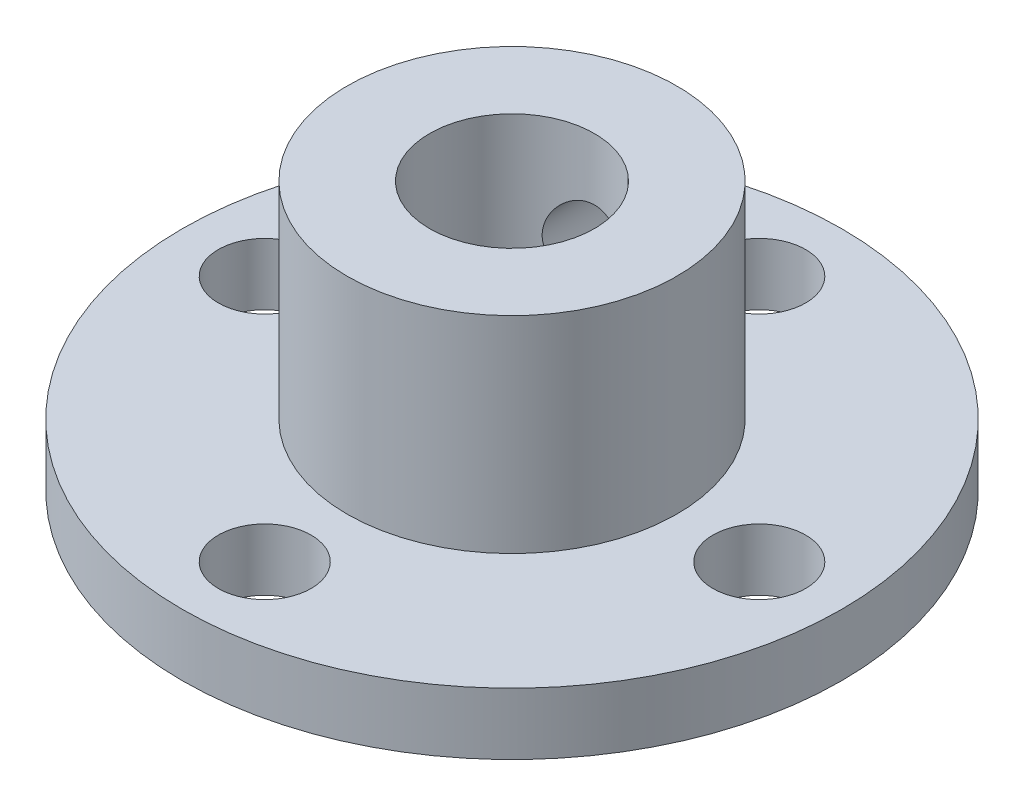
SolidWorks part; units mm, degrees
ref_plane "Front Plane" through (0, 0, 0) normal (0, 0, 1) x (1, 0, 0)
ref_plane "Top Plane" through (0, 0, 0) normal (0, 1, 0) x (1, 0, 0)
ref_plane "Right Plane" through (0, 0, 0) normal (1, 0, 0) x (0, 0, -1)
sketch "Sketch1" plane through (0, 0, 0) normal (0, 1, 0) x (1, 0, 0)
  circle A0 centre (0, 0) radius 16
  dimension "D1" = 32
extrude "Boss-Extrude1" add sketch "Sketch1" along normal blind 3
sketch "Sketch2" plane through (0, 3, 0) normal (0, 1, 0) x (1, 0, 0)
  circle A0 centre (0, 0) radius 8
  dimension "D1" = 16
extrude "Boss-Extrude2" add sketch "Sketch2" along normal blind 10
sketch "Sketch3" plane through (0, 13, 0) normal (0, 1, 0) x (1, 0, 0)
  circle A0 centre (0, 0) radius 4
  dimension "D1" = 8
extrude "Cut-Extrude1" cut sketch "Sketch3" against normal up to next
sketch "Sketch4" plane through (0, 3, 0) normal (0, 1, 0) x (1, 0, 0)
  circle A0 centre (0, 12) radius 2.25
  circle A1 centre (12, 0) radius 2.25
  circle A2 centre (0, -12) radius 2.25
  circle A3 centre (-12, 0) radius 2.25
  point P13 (0, 0)
  dimension "D1" = 4.5
  dimension "D2" = 12
  dimension "D3" = 4
extrude "Cut-Extrude2" cut sketch "Sketch4" against normal up to next
sketch "Sketch5" plane through (0, 0, 0) normal (0, 0, 1) x (1, 0, 0)
  line L4 (8, 13) -> (-8, 13) construction
  circle A0 centre (0, 8) radius 2
  dimension "D1" = 5
extrude "Cut-Extrude3" cut sketch "Sketch5" against normal up to next
